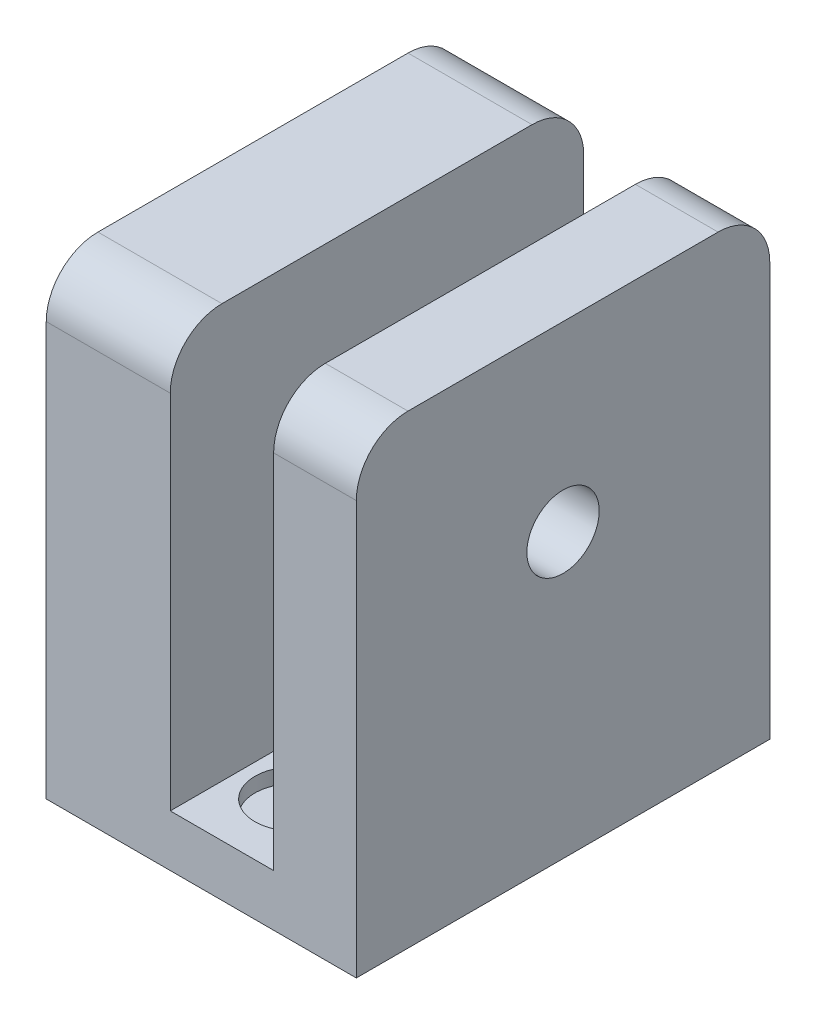
SolidWorks part; units mm, degrees
ref_plane "Front Plane" through (0, 0, 0) normal (0, 0, 1) x (1, 0, 0)
ref_plane "Top Plane" through (0, 0, 0) normal (0, 1, 0) x (1, 0, 0)
ref_plane "Right Plane" through (0, 0, 0) normal (1, 0, 0) x (0, 0, -1)
sketch "Sketch1" plane through (0, 0, 0) normal (0, 1, 0) x (1, 0, 0)
  line L1 (-15, -20) -> (15, -20)
  line L2 (-15, -20) -> (-15, 20)
  line L3 (-15, 20) -> (15, 20)
  line L4 (15, -20) -> (15, 20)
  line L5 (-15, -20) -> (15, 20) construction
  line L6 (-15, 20) -> (15, -20) construction
  point P0 (0, 0)
  dimension "D1" = 30
  dimension "D2" = 40
extrude "Boss-Extrude1" add sketch "Sketch1" along normal blind 45
sketch "Sketch2" plane through (0, 0, 20) normal (0, 0, 1) x (1, 0, 0)
  line L0 (-3, 45) -> (7, 45)
  line L1 (-3, 45) -> (-3, 5)
  line L2 (7, 45) -> (7, 5)
  line L3 (-3, 5) -> (7, 5)
  line L4 (-15, 45) -> (15, 45) construction
  line L5 (-15, 45) -> (-15, 0) construction
  line L6 (-15, 0) -> (15, 0) construction
  dimension "D1" = 10
  dimension "D2" = 12
  dimension "D3" = 5
extrude "Cut-Extrude1" cut sketch "Sketch2" against normal through all
sketch "Sketch3" plane through (-15, 0, 0) normal (-1, 0, 0) x (0, 0, 1)
  circle A0 centre (0, 27.3919) radius 3.5
  dimension "D1" = 7
extrude "Cut-Extrude2" cut sketch "Sketch3" against normal through all
sketch "Sketch4" plane through (-15, 0, 0) normal (-1, 0, 0) x (0, 0, 1)
  line L0 (-20, 45) -> (-20, 0) construction
  line L1 (-20, 45) -> (20, 45) construction
  line L2 (20, 45) -> (20, 0) construction
  line L3 (-20, 45) -> (-15, 45)
  line L4 (-20, 45) -> (-20, 40)
  line L5 (15, 45) -> (20, 45)
  line L6 (20, 45) -> (20, 40)
  arc A0 (-20, 40) -> (-15, 45) centre (-15, 40) cw
  arc A1 (15, 45) -> (20, 40) centre (15, 40) cw
  dimension "D1" = 5
  dimension "D2" = 5
extrude "Cut-Extrude3" cut sketch "Sketch4" against normal through all
hole_wizard "CBORE for M2 Hex Head Cap Screw1" positions "Sketch6" profile "Sketch5" counterbore size "M2" standard "ISO" end condition through all
sketch "Sketch6" plane through (0, 5, 0) normal (0, 1, 0) x (1, 0, 0)
  line L0 (-3, 20) -> (-3, -20) construction
  line L1 (-3, 20) -> (7, 20) construction
  line L2 (-3, -20) -> (7, -20) construction
  point P0 (2, -13)
  point P2 (2, 13)
  dimension "D1" = 5
  dimension "D2" = 5
  dimension "D3" = 7
  dimension "D4" = 7
sketch "Sketch5" plane through (2, 5, 13) normal (1, 0, 0) x (0, 0, 1)
  line L0 (0, 0) -> (0, 5)
  line L1 (0, 5) -> (1.2, 5)
  line L3 (1.2, 5) -> (1.2, 1.4)
  line L4 (1.2, 1.4) -> (3.8095, 1.4)
  line L5 (3.8095, 1.4) -> (3.8095, 0)
  line L7 (3.8095, 0) -> (0, 0)
  line L11 (0, -6.35) -> (0, 107.95) construction
  dimension "Thru Hole Dia." = 2.4
  dimension "Thru Hole Depth" = 5
  dimension "C'Bore Dia." = 7.619
  dimension "C'Bore Depth" = 1.4
